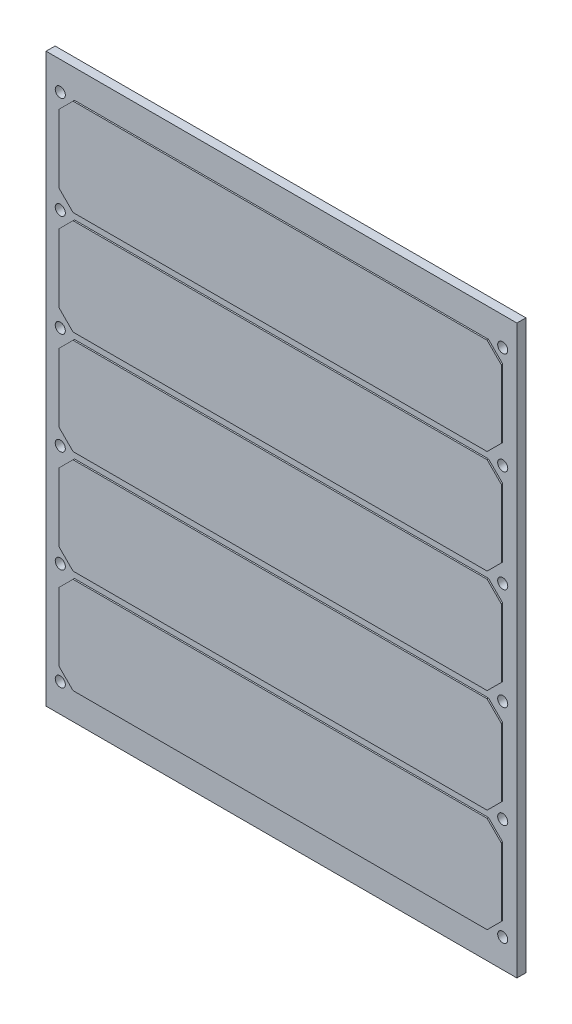
SolidWorks part; units mm, degrees
ref_plane "Front Plane" through (0, 0, 0) normal (0, 0, 1) x (1, 0, 0)
ref_plane "Top Plane" through (0, 0, 0) normal (0, 1, 0) x (1, 0, 0)
ref_plane "Right Plane" through (0, 0, 0) normal (1, 0, 0) x (0, 0, -1)
sketch "Sketch1" plane through (0, 0, 0) normal (0, 0, 1) x (1, 0, 0)
  line L1 (-41.5, -50) -> (41.5, -50)
  line L2 (-41.5, -50) -> (-41.5, 50)
  line L3 (-41.5, 50) -> (41.5, 50)
  line L4 (41.5, -50) -> (41.5, 50)
  line L5 (-41.5, -50) -> (41.5, 50) construction
  line L6 (-41.5, 50) -> (41.5, -50) construction
  point P0 (0, 0)
  dimension "D1" = 83
  dimension "D2" = 100
extrude "Boss-Extrude1" add sketch "Sketch1" along normal blind 1.5875
sketch "Sketch2" plane through (0, 0, 1.5875) normal (0, 0, 1) x (1, 0, 0)
  line L0 (-36.5, 45) -> (36.5, 45)
  line L1 (36.5, 45) -> (39, 42.5)
  line L2 (39, 42.5) -> (39, 30.5)
  line L3 (36.5, 28) -> (-36.5, 28)
  line L4 (-39, 30.5) -> (-39, 42.5)
  line L5 (-39, 42.5) -> (-36.5, 45)
  line L6 (0, 0) -> (0, 50) construction
  line L7 (41.5, 50) -> (-41.5, 50) construction
  line L8 (-36.5, 28) -> (-39, 30.5)
  line L9 (39, 30.5) -> (36.5, 28)
  line L10 (-36.5, 26.75) -> (36.5, 26.75)
  line L11 (36.5, 26.75) -> (39, 24.25)
  line L12 (39, 24.25) -> (39, 12.25)
  line L13 (36.5, 9.75) -> (-36.5, 9.75)
  line L14 (-39, 12.25) -> (-39, 24.25)
  line L15 (-39, 24.25) -> (-36.5, 26.75)
  line L16 (-36.5, 9.75) -> (-39, 12.25)
  line L17 (39, 12.25) -> (36.5, 9.75)
  line L18 (-36.5, 8.5) -> (36.5, 8.5)
  line L19 (36.5, 8.5) -> (39, 6)
  line L20 (39, 6) -> (39, -6)
  line L21 (36.5, -8.5) -> (-36.5, -8.5)
  line L22 (-39, -6) -> (-39, 6)
  line L23 (-39, 6) -> (-36.5, 8.5)
  line L24 (-36.5, -8.5) -> (-39, -6)
  line L25 (39, -6) -> (36.5, -8.5)
  line L26 (-36.5, -9.75) -> (36.5, -9.75)
  line L27 (36.5, -9.75) -> (39, -12.25)
  line L28 (39, -12.25) -> (39, -24.25)
  line L29 (36.5, -26.75) -> (-36.5, -26.75)
  line L30 (-39, -24.25) -> (-39, -12.25)
  line L31 (-39, -12.25) -> (-36.5, -9.75)
  line L32 (-36.5, -26.75) -> (-39, -24.25)
  line L33 (39, -24.25) -> (36.5, -26.75)
  line L34 (-36.5, -28) -> (36.5, -28)
  line L35 (36.5, -28) -> (39, -30.5)
  line L36 (39, -30.5) -> (39, -42.5)
  line L37 (36.5, -45) -> (-36.5, -45)
  line L38 (-39, -42.5) -> (-39, -30.5)
  line L39 (-39, -30.5) -> (-36.5, -28)
  line L40 (-36.5, -45) -> (-39, -42.5)
  line L41 (39, -42.5) -> (36.5, -45)
  line L42 (-41.5, -50) -> (41.5, -50) construction
  point P4 (39, 28)
  point P5 (-39, 28)
  point P20 (39, 9.75)
  point P21 (-39, 9.75)
  point P30 (39, -8.5)
  point P31 (-39, -8.5)
  point P40 (39, -26.75)
  point P41 (-39, -26.75)
  point P50 (39, -45)
  point P51 (-39, -45)
  dimension "D1" = 78
  dimension "D2" = 2.5
  dimension "D3" = 45
  dimension "D4" = 17
  dimension "D5" = 5
  dimension "D7" = 5
  dimension "D6" = 5
extrude "Boss-Extrude2" add sketch "Sketch2" along normal blind 0.25
hole_wizard "#0 Clearance Hole1" positions "Sketch4" profile "Sketch3" hole size "#0" standard "ANSI Inch"
sketch "Sketch4" plane through (0, 0, 1.5875) normal (0, 0, 1) x (1, 0, 0)
  line L0 (-41.5, 50) -> (-41.5, -50) construction
  line L1 (41.5, 50) -> (-41.5, 50) construction
  line L2 (-41.5, -50) -> (41.5, -50) construction
  line L3 (0, 50) -> (0, -50) construction
  point P56 (-39, 45)
  point P79 (-39, 27)
  point P80 (-39, 9)
  point P81 (-39, -9)
  point P82 (-39, -27)
  point P83 (-39, -45)
  point P91 (39, -45)
  point P92 (39, -27)
  point P93 (39, -9)
  point P94 (39, 9)
  point P95 (39, 27)
  point P96 (39, 45)
  dimension "D1" = 2.5
  dimension "D2" = 5
  dimension "D3" = 6
  dimension "D4" = 5
sketch "Sketch3" plane through (-39, 45, 1.5875) normal (1, 0, 0) x (0, -1, 0)
  line L0 (0, 0) -> (0, 3.7092)
  line L1 (0, 3.7092) -> (0.889, 3.175)
  line L2 (0.889, 3.175) -> (0.889, 0)
  line L5 (0.889, 0) -> (0, 0)
  line L10 (0, 3.7092) -> (-0.889, 3.175) construction
  line L11 (0, -6.35) -> (0, 107.95) construction
  dimension "Hole Dia." = 1.778
  dimension "Hole Depth" = 3.175
  dimension "Drill Angle" = 118
